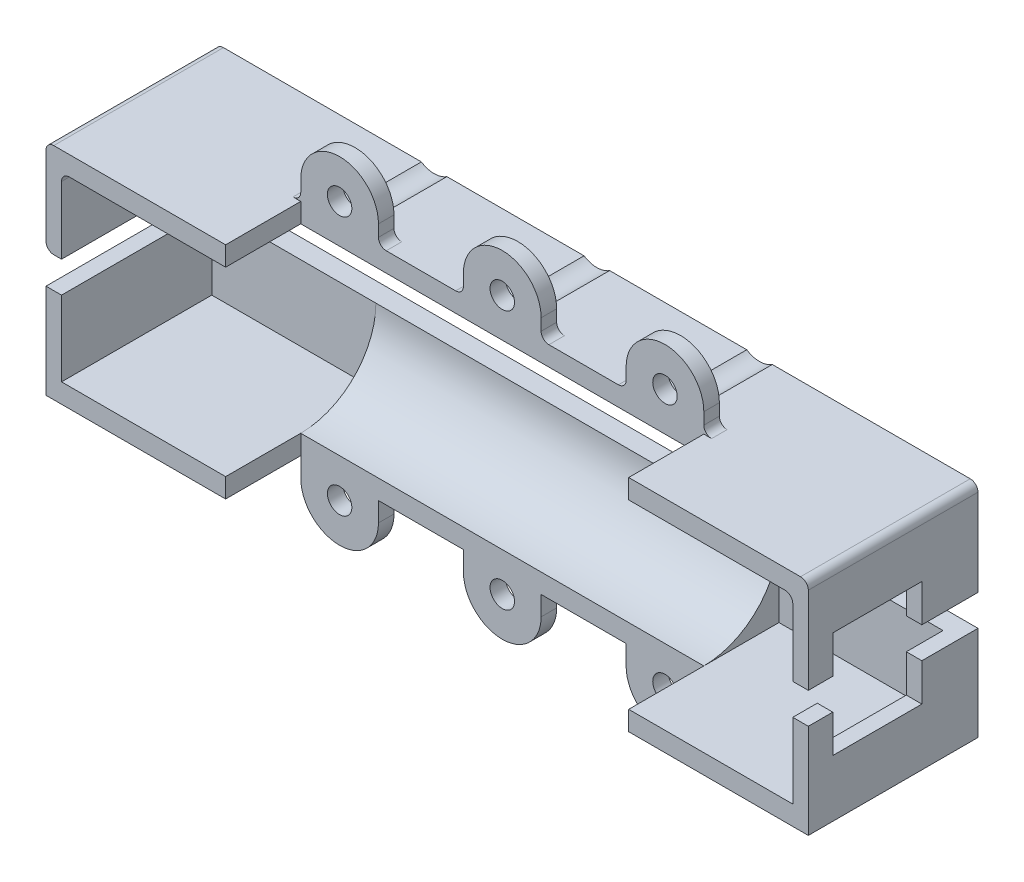
SolidWorks part; units mm, degrees
material "ABS"
ref_plane "X-Y Datum" through (0, 0, 0) normal (0, 0, 1) x (1, 0, 0)
ref_plane "X-Z Datum" through (0, 0, 0) normal (0, 1, 0) x (1, 0, 0)
ref_plane "Y-Z Datum" through (0, 0, 0) normal (1, 0, 0) x (0, 0, -1)
sketch "Sketch1" plane through (0, 0, 0) normal (1, 0, 0) x (0, 0, -1)
  line L1 (34.2074, 10.3366) -> (37.3824, 10.3366)
  line L4 (37.3824, 10.3366) -> (37.3824, -5.1193)
  line L5 (37.3824, -5.1193) -> (21.9265, -5.1193)
  line L6 (21.9265, -5.1193) -> (21.9265, -1.9443)
  arc A0 (21.9265, -1.9443) -> (34.2074, 10.3366) centre (21.9265, 10.3366) ccw
extrude "Boss-Extrude1" add sketch "Sketch1" along normal blind 65.8876
sketch "Sketch2" plane through (65.8876, 0, 0) normal (1, 0, 0) x (0, 0, -1)
  line L0 (37.3824, -1.9443) -> (37.3824, 10.3366)
  line L1 (37.3824, -5.1193) -> (9.6464, -5.1193)
  line L2 (37.3824, -5.1193) -> (37.3824, -1.9443)
  line L3 (34.2074, -1.9443) -> (9.6464, -1.9443)
  line L4 (9.6464, -5.1193) -> (9.6464, -1.9443)
  line L5 (37.3824, 10.3366) -> (34.2074, 10.3366)
  line L6 (34.2074, 10.3366) -> (34.2074, -1.9443)
extrude "Boss-Extrude2" add sketch "Sketch2" along normal blind 29.3624
sketch "Sketch3" plane through (95.25, 0, 0) normal (1, 0, 0) x (0, 0, -1)
  line L0 (28.2074, 4.1961) -> (13.6464, 4.1961)
  line L1 (34.2074, -1.9443) -> (28.2074, -1.9443)
  line L2 (34.2074, -1.9443) -> (34.2074, 10.3366)
  line L3 (34.2074, 10.3366) -> (28.2074, 10.3366)
  line L4 (28.2074, 4.1961) -> (28.2074, 10.3366)
  line L5 (9.6464, 4.1961) -> (9.6464, -1.9443)
  line L6 (9.6464, -1.9443) -> (28.2074, -1.9443)
  line L7 (9.6464, 4.1961) -> (9.6464, 10.3366)
  line L8 (9.6464, 10.3366) -> (13.6464, 10.3366)
  line L9 (13.6464, 10.3366) -> (13.6464, 4.1961)
extrude "Boss-Extrude3" add sketch "Sketch3" against normal blind 2.54
sketch "Sketch4" plane through (0, 0, -21.9265) normal (0, 0, 1) x (1, 0, 0)
  line L1 (0, -8.2943) -> (0, -5.1193)
  line L4 (12.7, -8.2943) -> (12.7, -5.1193)
  line L10 (12.7, -5.1193) -> (0, -5.1193)
  line L12 (32.9438, -5.1193) -> (32.9438, -8.2943) construction
  line L23 (0, -5.1193) -> (3.175, -5.1193) construction
  line L24 (65.8876, -5.1193) -> (0, -5.1193) construction
  line L27 (6.35, -5.1193) -> (6.35, -8.2943) construction
  line L30 (26.5938, -8.2943) -> (26.5938, -5.1193)
  line L31 (26.5938, -5.1193) -> (39.2938, -5.1193)
  line L32 (39.2938, -5.1193) -> (39.2938, -8.2943)
  line L33 (59.5376, -5.1193) -> (59.5376, -8.2943) construction
  line L34 (65.8876, -5.1193) -> (62.7126, -5.1193) construction
  line L35 (53.1876, -5.1193) -> (65.8876, -5.1193)
  line L36 (53.1876, -8.2943) -> (53.1876, -5.1193)
  line L37 (65.8876, -8.2943) -> (65.8876, -5.1193)
  arc A18 (0, -8.2943) -> (12.7, -8.2943) centre (6.35, -8.2943) ccw
  circle A19 centre (6.35, -8.2943) radius 2
  circle A20 centre (32.9438, -8.2943) radius 2
  arc A21 (26.5938, -8.2943) -> (39.2938, -8.2943) centre (32.9438, -8.2943) ccw
  circle A22 centre (59.5376, -8.2943) radius 2
  arc A23 (65.8876, -8.2943) -> (53.1876, -8.2943) centre (59.5376, -8.2943) cw
extrude "Boss-Extrude4" add sketch "Sketch4" against normal blind 2.54
ref_plane "Plane1" through (32.9438, 0, 0) normal (1, 0, 0) x (0, 0, -1)
mirror "Mirror1" about plane through (32.9438, 0, 0) normal (1, 0, 0) of "Boss-Extrude2"
sketch "Sketch6" plane through (-29.3624, 0, 0) normal (-1, 0, 0) x (0, 0, 1)
  line L0 (-9.6464, 10.3366) -> (-9.6464, -1.9443) construction
  line L1 (-34.2074, -1.9443) -> (-9.6464, -1.9443)
  line L2 (-34.2074, -1.9443) -> (-34.2074, 10.3366)
  line L3 (-34.2074, 10.3366) -> (-9.6464, 10.3366)
  line L4 (-9.6464, -1.9443) -> (-9.6464, 10.3366)
  line L5 (-13.6464, 10.3366) -> (-9.6464, 10.3366) construction
extrude "Boss-Extrude5" add sketch "Sketch6" against normal blind 2.54
ref_plane "Plane2" through (0, 12.8766, 0) normal (0, 1, 0) x (1, 0, 0)
mirror "Mirror3" about plane through (0, 12.8766, 0) normal (0, 1, 0) of bodies 106
fillet "Fillet1" radius 1.27 3 edges at (-29.3624, 30.8725, -23.5144) (-29.3624, 15.4166, -23.5144) (95.25, 30.8725, -23.5144)
fillet "Fillet2" radius 1.27 6 edges at (0, 30.8725, -23.1965) (12.7, 30.8725, -23.1965) (26.5938, 30.8725, -23.1965) (39.2938, 30.8725, -23.1965) (65.8876, 30.8725, -23.1965) (53.1876, 30.8725, -23.1965)
fillet "Fillet3" radius 1.27 2 edges at (-26.8224, 27.6975, -21.9269) (92.71, 27.6975, -21.9269)
sketch "Sketch7" plane through (0, 0, -37.3824) normal (0, 0, -1) x (-1, 0, 0)
  circle A0 centre (-59.5376, 34.0475) radius 3.8
  circle A1 centre (-32.9438, 34.0475) radius 3.8
  circle A2 centre (-6.35, 34.0475) radius 3.8
extrude "Cut-Extrude1" cut sketch "Sketch7" against normal up to surface (12.9159 mm away) up to face at (57.5376, 34.0475, -24.4665)
